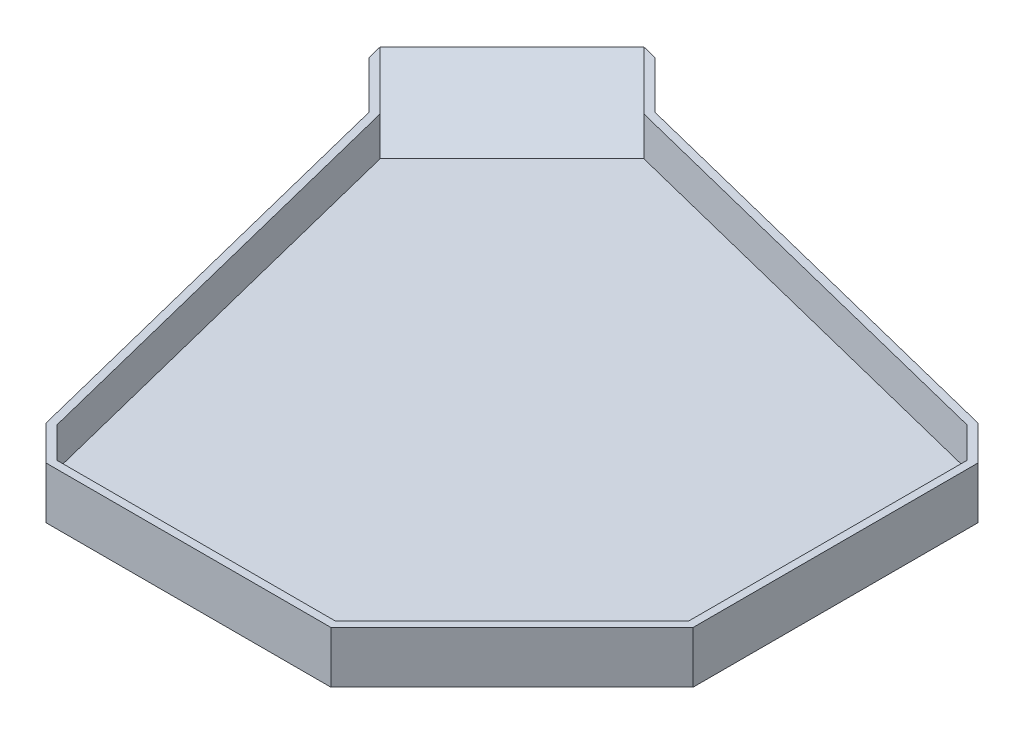
SolidWorks part; units mm, degrees
ref_plane "前视基准面" through (0, 0, 0) normal (0, 0, 1) x (1, 0, 0)
ref_plane "上视基准面" through (0, 0, 0) normal (0, 1, 0) x (1, 0, 0)
ref_plane "右视基准面" through (0, 0, 0) normal (1, 0, 0) x (0, 0, -1)
other "Configuration Table"
sketch "草图1" plane through (0, 0, 0) normal (0, 1, 0) x (1, 0, 0)
  line L0 (-50, 10) -> (-10, 50)
  line L1 (10, 10) -> (-10, 10) construction
  line L2 (10, 10) -> (10, -10) construction
  line L3 (10, -10) -> (-10, -10) construction
  line L4 (-10, 10) -> (-10, -10) construction
  line L5 (10, 10) -> (-10, -10) construction
  line L6 (10, -10) -> (-10, 10) construction
  line L7 (-50, 10) -> (0, -190) construction
  line L9 (190, 0) -> (-10, 50) construction
  line L10 (0, -190) -> (120, -190) construction
  line L11 (190, 0) -> (190, -120) construction
  line L12 (190, -120) -> (120, -190)
  line L13 (-3.3333, -176.6667) -> (10, -190)
  line L14 (176.6667, 3.3333) -> (190, -10)
  line L15 (-50, 10) -> (-3.3333, -176.6667)
  line L16 (10, -190) -> (120, -190)
  line L17 (-10, 50) -> (176.6667, 3.3333)
  line L18 (190, -10) -> (190, -120)
  circle A0 centre (0, 0) radius 190 construction
  circle A1 centre (-10, 10) radius 40 construction
  dimension "D1" = 20
  dimension "D3" = 80
  dimension "D6" = 10
  dimension "D4" = 380
  dimension "D2" = 20
  dimension "D5" = 10
extrude "凸台-拉伸1" add sketch "草图1" along normal blind 5
sketch "草图2" plane through (0, 0, 0) normal (0, -1, 0) x (1, 0, 0)
  line L0 (-50, -10) -> (-39.3934, 0.6066)
  line L1 (-39.3934, 0.6066) -> (0.6066, -39.3934)
  line L2 (0.6066, -39.3934) -> (-10, -50)
  line L3 (-50, -10) -> (-10, -50)
  dimension "D1" = 15
extrude "凸台-拉伸2" add sketch "草图2" along normal blind 15
sketch "草图3" plane through (20, 0, -20) normal (0.7071, 0, -0.7071) x (-0.7071, 0, -0.7071)
  line L0 (27.4264, -7.5) -> (42.4264, -7.5) construction
  line L1 (27.4264, -15) -> (27.4264, 0) construction
  line L3 (34.9264, -15) -> (34.9264, 0) construction
  line L4 (42.4264, -15) -> (27.4264, -15) construction
  line L5 (42.4264, 0) -> (27.4264, 0) construction
  line L8 (27.4264, -7.5) -> (27.4264, -15)
  line L9 (27.4264, -15) -> (34.9264, -15)
  circle A0 centre (34.9264, -7.5) radius 7.5 construction
  arc A2 (27.4264, -7.5) -> (34.9264, -15) centre (34.9264, -7.5) ccw
extrude "切除-拉伸1" cut sketch "草图3" against normal blind 60
sketch "草图4" plane through (20, 0, -20) normal (0.7071, 0, -0.7071) x (-0.7071, 0, -0.7071)
  line L0 (27.4264, -7.5) -> (42.4264, -7.5) construction
  line L1 (42.4264, -15) -> (42.4264, 0) construction
  line L2 (34.9264, -15) -> (42.4264, -15)
  line L3 (42.4264, -15) -> (42.4264, -7.5)
  arc A0 (42.4264, -7.5) -> (34.9264, -15) centre (34.9264, -7.5) cw
  circle A1 centre (34.9264, -7.5) radius 4
extrude "切除-拉伸2" cut sketch "草图4" against normal blind 60
sketch "草图5" plane through (0, 5, 0) normal (0, 1, 0) x (1, 0, 0)
  line L2 (-0.6244, -175.1329) -> (11.2426, -187)
  line L3 (11.2426, -187) -> (118.7574, -187)
  line L4 (118.7574, -187) -> (187, -118.7574)
  line L5 (187, -118.7574) -> (187, -11.2426)
  line L6 (187, -11.2426) -> (175.1329, 0.6244)
  line L7 (175.1329, 0.6244) -> (8.6752, 42.2389)
  line L10 (176.6667, 3.3333) -> (190, -10)
  line L11 (190, -10) -> (190, -120)
  line L12 (190, -120) -> (120, -190)
  line L13 (120, -190) -> (10, -190)
  line L14 (10, -190) -> (-3.3333, -176.6667)
  line L16 (-10, 50) -> (-50, 10) construction
  line L17 (-50, 10) -> (-46.362, -4.5521) construction
  line L18 (-50, 10) -> (-3.3333, -176.6667) construction
  line L19 (-46.362, -4.5521) -> (-3.3333, -176.6667)
  line L20 (-0.6244, -175.1329) -> (-42.2389, -8.6752)
  line L21 (-42.2389, -8.6752) -> (-46.362, -4.5521)
  line L22 (-46.362, -4.5521) -> (4.5521, 46.362) construction
  line L23 (176.6667, 3.3333) -> (-10, 50) construction
  line L24 (8.6752, 42.2389) -> (4.5521, 46.362)
  line L25 (4.5521, 46.362) -> (176.6667, 3.3333)
  dimension "D1" = 15
  dimension "D2" = 3
  dimension "D3" = 3
  dimension "D4" = 3
  dimension "D5" = 3
  dimension "D6" = 3
  dimension "D7" = 3
  dimension "D8" = 3
extrude "凸台-拉伸3" add sketch "草图5" along normal blind 15
sketch "草图6" plane through (-30, 0, -30) normal (-0.7071, 0, -0.7071) x (-0.7071, 0, 0.7071)
  line L0 (28.2843, 0) -> (127.2792, 0) construction
  line L5 (-36.0017, 5) -> (36.0017, 5)
  line L6 (-36.0017, 5) -> (-36.0017, 0)
  line L7 (-36.0017, 0) -> (36.0017, 0)
  line L8 (36.0017, 5) -> (36.0017, 0)
  line L9 (36.0017, 20) -> (36.0017, 5) construction
extrude "凸台-拉伸4" add sketch "草图6" against normal mid plane 26
sketch "草图7" plane through (0, 20, 0) normal (0, 1, 0) x (1, 0, 0)
  line L0 (-42.2389, -8.6752) -> (-64.6494, 13.7353)
  line L1 (-64.6494, 13.7353) -> (-63.2352, 8.0785)
  line L2 (-63.2352, 8.0785) -> (-44.9478, -10.209)
  line L3 (-46.362, -4.5521) -> (-3.3333, -176.6667) construction
  line L4 (-44.9478, -10.209) -> (-42.2389, -8.6752)
  line L5 (8.6752, 42.2389) -> (-13.7353, 64.6494)
  line L6 (-13.7353, 64.6494) -> (-8.0785, 63.2352)
  line L7 (-8.0785, 63.2352) -> (10.209, 44.9478)
  line L8 (10.209, 44.9478) -> (8.6752, 42.2389)
  line L9 (-0.6244, -175.1329) -> (-42.2389, -8.6752) construction
  line L10 (8.6752, 42.2389) -> (175.1329, 0.6244) construction
  line L11 (176.6667, 3.3333) -> (4.5521, 46.362) construction
  point P18 (12.7121, 42.2389)
  point P19 (10.2297, 44.9426)
  dimension "D1" = 3
  dimension "D2" = 3
extrude "凸台-拉伸5" add sketch "草图7" against normal blind 20
sketch "草图8" plane through (25.4571, 0, -25.4571) normal (-0.7071, 0, 0.7071) x (0.7071, 0, 0.7071)
  line L0 (-55.4264, 20) -> (-23.7331, 5)
  line L1 (-23.7331, 5) -> (-55.4264, 5)
  line L2 (-55.4264, 5) -> (-55.4264, 20)
extrude "凸台-拉伸6" add sketch "草图8" along normal blind 72
